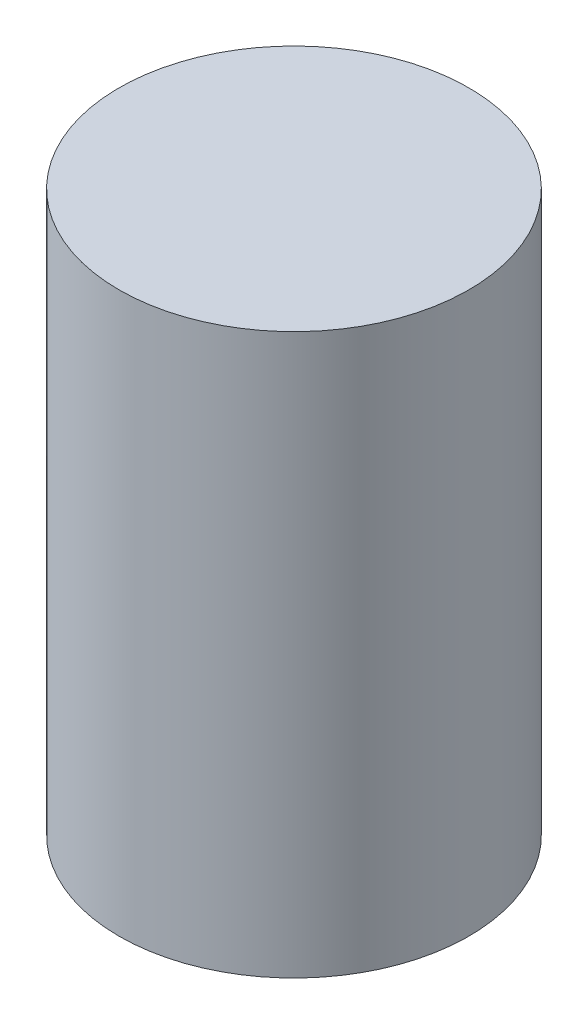
SolidWorks part; units mm, degrees
material "Polyurethane Foam Flexible"
ref_plane "Front Plane" through (0, 0, 0) normal (0, 0, 1) x (1, 0, 0)
ref_plane "Top Plane" through (0, 0, 0) normal (0, 1, 0) x (1, 0, 0)
ref_plane "Right Plane" through (0, 0, 0) normal (1, 0, 0) x (0, 0, -1)
sketch "Sketch1" plane through (0, 0, 0) normal (0, 1, 0) x (1, 0, 0)
  circle A0 centre (0, 0) radius 63.5
  dimension "D1" = 127
extrude "Boss-Extrude1" add sketch "Sketch1" along normal blind 203.2
